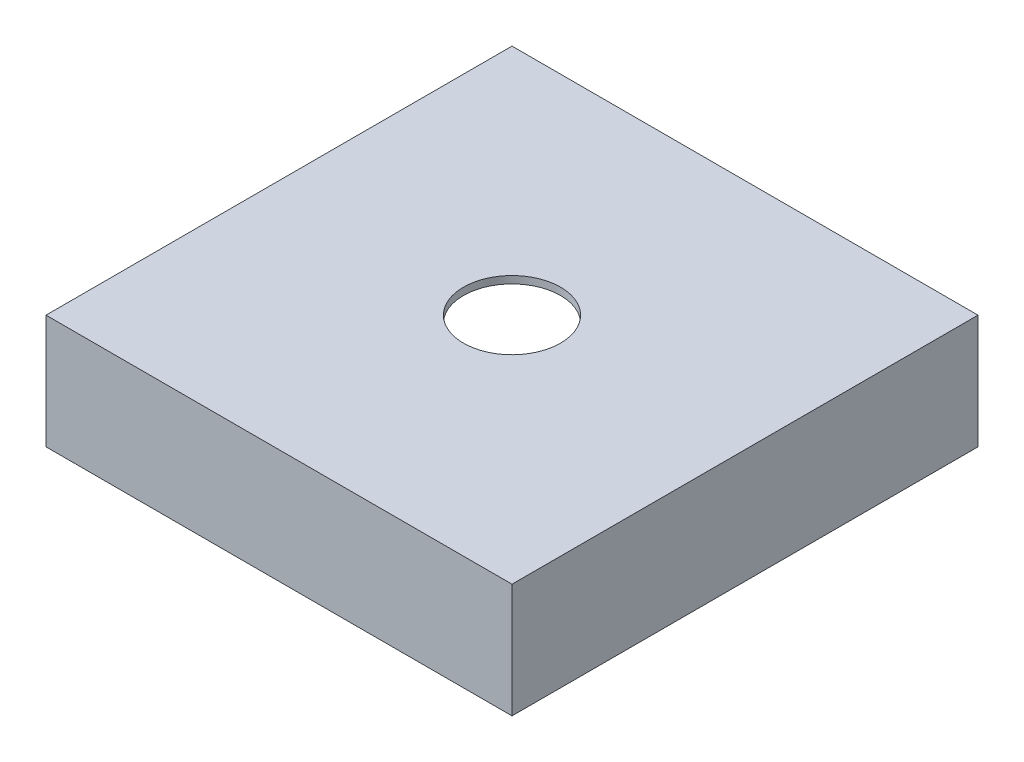
SolidWorks part; units mm, degrees
ref_plane "Front Plane" through (0, 0, 0) normal (0, 0, 1) x (1, 0, 0)
ref_plane "Top Plane" through (0, 0, 0) normal (0, 1, 0) x (1, 0, 0)
ref_plane "Right Plane" through (0, 0, 0) normal (1, 0, 0) x (0, 0, -1)
sketch "Sketch1" plane through (0, 0, 0) normal (0, 1, 0) x (1, 0, 0)
  line L1 (1589.699, -285.5487) -> (2199.299, -285.5487)
  line L2 (1589.699, -285.5487) -> (1589.699, -895.1487)
  line L3 (1589.699, -895.1487) -> (2199.299, -895.1487)
  line L4 (2199.299, -285.5487) -> (2199.299, -895.1487)
  circle A8 centre (1894.499, -590.3487) radius 63.5
extrude "Boss-Extrude1" add sketch "Sketch1" along normal blind 9.525
sketch "Sketch2" plane through (0, 0, 0) normal (0, -1, 0) x (1, 0, 0)
  line L0 (1589.699, 285.5487) -> (1589.699, 323.6487)
  line L1 (1589.699, 285.5487) -> (1589.699, 895.1487) construction
  line L3 (1589.699, 285.5487) -> (1589.699, 437.9487)
  line L4 (1589.699, 285.5487) -> (1589.699, 895.1487) construction
  line L6 (1627.799, 323.6487) -> (1627.799, 437.9487)
  line L7 (1589.699, 285.5487) -> (1742.099, 285.5487)
  line L8 (1742.099, 857.0487) -> (2046.899, 857.0487)
  line L9 (1894.499, 285.5487) -> (1589.699, 285.5487) construction
  line L11 (1742.099, 323.6487) -> (1627.799, 323.6487)
  line L12 (1589.699, 895.1487) -> (1589.699, 742.7487)
  line L14 (1627.799, 742.7487) -> (1627.799, 857.0487)
  line L15 (1627.799, 857.0487) -> (1742.099, 857.0487)
  line L17 (1589.699, 895.1487) -> (1742.099, 895.1487)
  line L18 (2199.299, 895.1487) -> (2046.899, 895.1487)
  line L20 (2046.899, 857.0487) -> (2161.199, 857.0487)
  line L21 (2161.199, 857.0487) -> (2161.199, 742.7487)
  line L23 (2199.299, 895.1487) -> (2199.299, 742.7487)
  line L24 (2199.299, 285.5487) -> (2199.299, 437.9487)
  line L26 (2161.199, 437.9487) -> (2161.199, 323.6487)
  line L27 (2161.199, 323.6487) -> (2046.899, 323.6487)
  line L29 (2199.299, 285.5487) -> (2046.899, 285.5487)
  line L30 (1742.099, 895.1487) -> (2046.899, 895.1487)
  line L31 (1589.699, 742.7487) -> (1589.699, 437.9487)
  line L32 (1627.799, 437.9487) -> (1627.799, 742.7487)
  line L33 (1742.099, 323.6487) -> (2046.899, 323.6487)
  line L34 (1742.099, 285.5487) -> (2046.899, 285.5487)
  line L35 (2161.199, 437.9487) -> (2161.199, 742.7487)
  line L36 (2199.299, 437.9487) -> (2199.299, 742.7487)
  point P35 (1894.499, 590.3487)
  dimension "D1" = 4
extrude "Boss-Extrude2" add sketch "Sketch2" along normal blind 139.7
sketch "Sketch4" plane through (0, 9.525, 0) normal (0, 1, 0) x (1, 0, 0)
  circle A0 centre (1894.499, -590.3487) radius 44.45
  circle A1 centre (1894.499, -590.3487) radius 55.0891
  circle A2 centre (1894.499, -590.3487) radius 41.275
